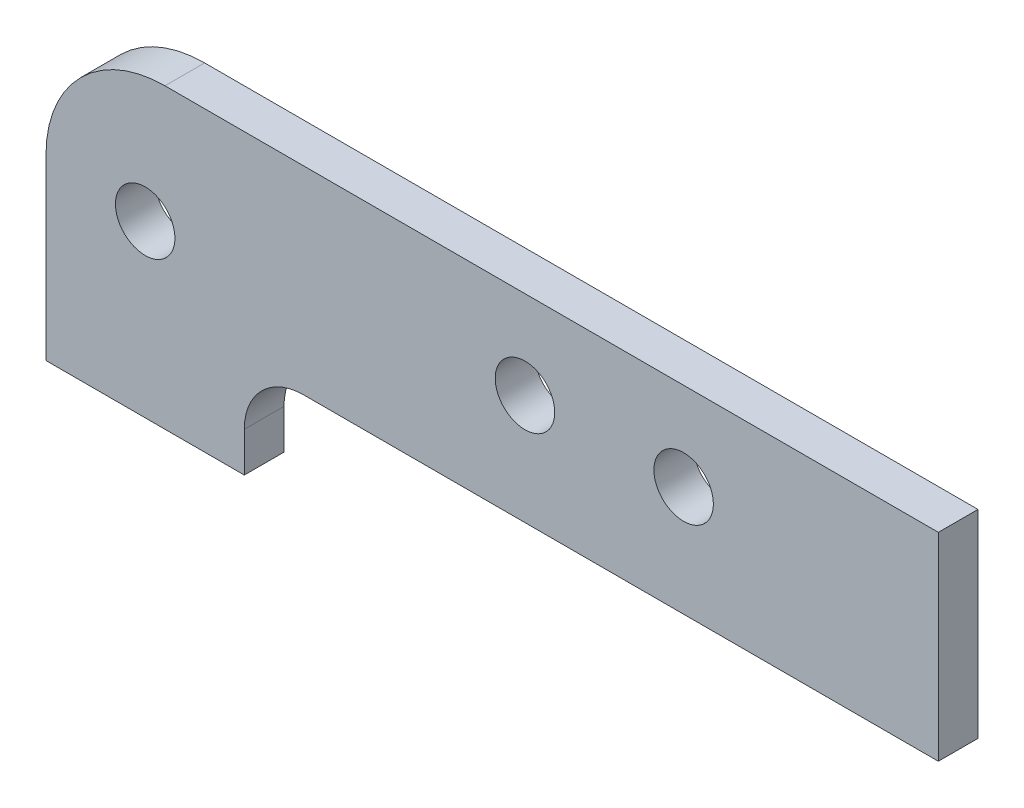
SolidWorks part; units mm, degrees
material "Thornel Mat VMA"
ref_plane "前视基准面" through (0, 0, 0) normal (0, 0, 1) x (1, 0, 0)
ref_plane "上视基准面" through (0, 0, 0) normal (0, 1, 0) x (1, 0, 0)
ref_plane "右视基准面" through (0, 0, 0) normal (1, 0, 0) x (0, 0, -1)
sketch "草图1" plane through (0, 0, 0) normal (0, 0, 1) x (1, 0, 0)
  line L0 (-17.5, -5) -> (-17.5, 5) construction
  line L1 (17.5, 5) -> (-17.5, 5)
  line L2 (17.5, 5) -> (17.5, -5)
  line L3 (17.5, -5) -> (-14.5, -5)
  line L5 (17.5, 5) -> (-17.5, -5) construction
  line L6 (17.5, -5) -> (-17.5, 5) construction
  line L7 (-17.5, 5) -> (-21.5, 5)
  line L8 (-17.5, -8) -> (-17.5, -10)
  line L9 (-17.5, -10) -> (-27.5, -10)
  line L10 (-27.5, -1) -> (-27.5, -10)
  arc A0 (-14.5, -5) -> (-17.5, -8) centre (-14.5, -8) ccw
  arc A1 (-21.5, 5) -> (-27.5, -1) centre (-21.5, -1) ccw
  point P0 (0, 0)
  dimension "D4" = 3
  dimension "D5" = 6
  dimension "D1" = 10
  dimension "D2" = 35
  dimension "D3" = 15
extrude "凸台-拉伸1" add sketch "草图1" along normal blind 2
hole_wizard "孔1" positions "草图2" profile "草图3" legacy end condition through all
sketch "草图2" plane through (0, 0, 2) normal (0, 0, 1) x (1, 0, 0)
  point P0 (-22.4984, -1.4104)
sketch "草图3" plane through (-22.4984, -1.4104, 2) normal (1, 0, 0) x (0, -1, 0)
  line L0 (0, 0) -> (0, 2)
  line L1 (0, 2) -> (1.5, 2)
  line L2 (1.5, 2) -> (1.5, 0)
  line L3 (1.5, 0) -> (0, 0)
  line L4 (0, 110) -> (0, -10) construction
  dimension "直径" = 3
  dimension "深度" = 2
hole_wizard "孔2" positions "草图4" profile "草图5" legacy end condition through all
sketch "草图4" plane through (0, 0, 2) normal (0, 0, 1) x (1, 0, 0)
  point P0 (4.655, 0.5564)
  point P2 (-3.345, 0.5564)
sketch "草图5" plane through (4.655, 0.5564, 2) normal (1, 0, 0) x (0, -1, 0)
  line L0 (0, 0) -> (0, 2)
  line L1 (0, 2) -> (1.5, 2)
  line L2 (1.5, 2) -> (1.5, 0)
  line L3 (1.5, 0) -> (0, 0)
  line L4 (0, 110) -> (0, -10) construction
  dimension "直径" = 3
  dimension "深度" = 2
